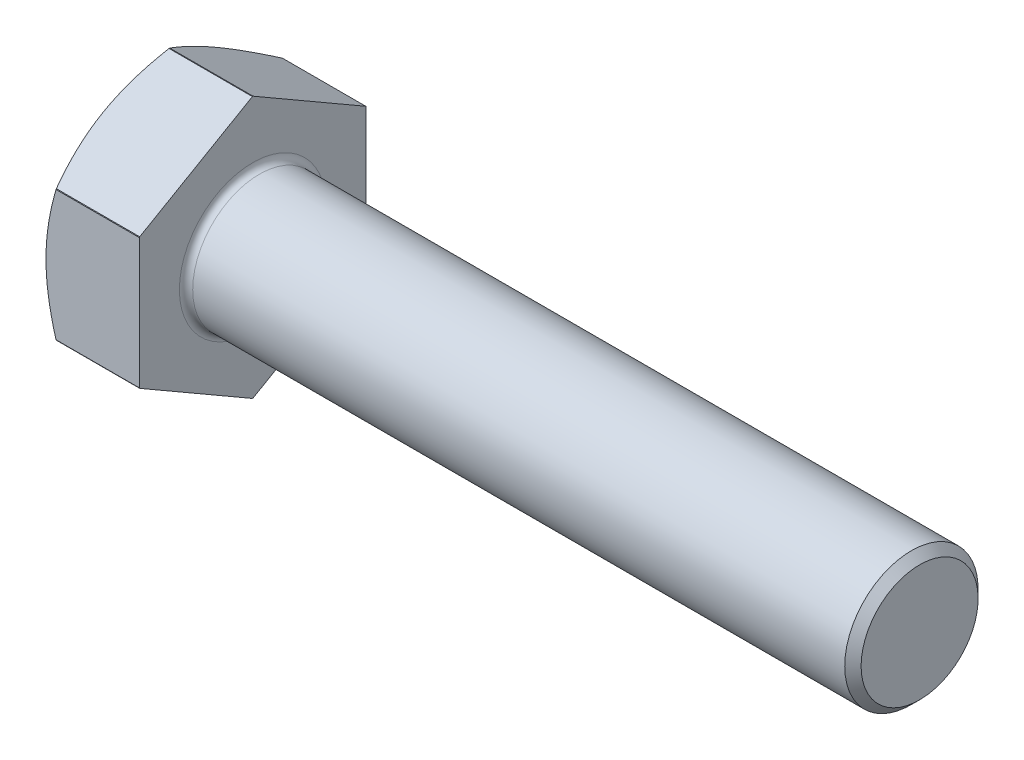
SolidWorks part; units mm, degrees
ref_plane "Front/Back" through (0, 0, 0) normal (0, 0, 1) x (1, 0, 0)
ref_plane "Top/Bottom" through (0, 0, 0) normal (0, 1, 0) x (1, 0, 0)
ref_plane "Right/Left" through (0, 0, 0) normal (1, 0, 0) x (0, 0, -1)
ref_plane "Plane1" through (0, 0, 0) normal (0, 0, 1) x (1, 0, 0)
sketch "Sketch1" plane through (0, 0, 0) normal (0, 0, 1) x (1, 0, 0)
  line L0 (-7, 0) -> (-7, 8.5)
  line L1 (-7, 8.5) -> (-6.2494, 9.8)
  line L2 (-6.2494, 9.8) -> (0, 9.8)
  line L3 (0, 9.8) -> (0, 5.5)
  line L4 (0.5, 5) -> (49.3865, 5)
  line L5 (49.3865, 5) -> (50, 4.3865)
  line L6 (50, 4.3865) -> (50, 0)
  line L7 (50, 0) -> (-7, 0)
  line L8 (50, 0) -> (-7, 0) construction
  arc A0 (0, 5.5) -> (0.5, 5) centre (0.5, 5.5) ccw
revolve "Revolve1" add sketch "Sketch1" angle 360 about L8
ref_plane "Plane2" through (0, 0, 0) normal (1, 0, 0) x (0, 0, -1)
sketch "Sketch2" plane through (0, 0, 0) normal (1, 0, 0) x (0, 0, -1)
  line L0 (-19.6, -19.6) -> (19.6, -19.6)
  line L1 (19.6, -19.6) -> (19.6, 19.6)
  line L2 (19.6, 19.6) -> (-19.6, 19.6)
  line L3 (-19.6, 19.6) -> (-19.6, -19.6)
  line L4 (-8.5, 4.9075) -> (-8.5, -4.9075)
  line L5 (-8.5, -4.9075) -> (0, -9.815)
  line L6 (0, -9.815) -> (8.5, -4.9075)
  line L7 (8.5, -4.9075) -> (8.5, 4.9075)
  line L8 (8.5, 4.9075) -> (0, 9.815)
  line L9 (0, 9.815) -> (-8.5, 4.9075)
extrude "Cut-Extrude1" cut sketch "Sketch2" against normal blind 7
